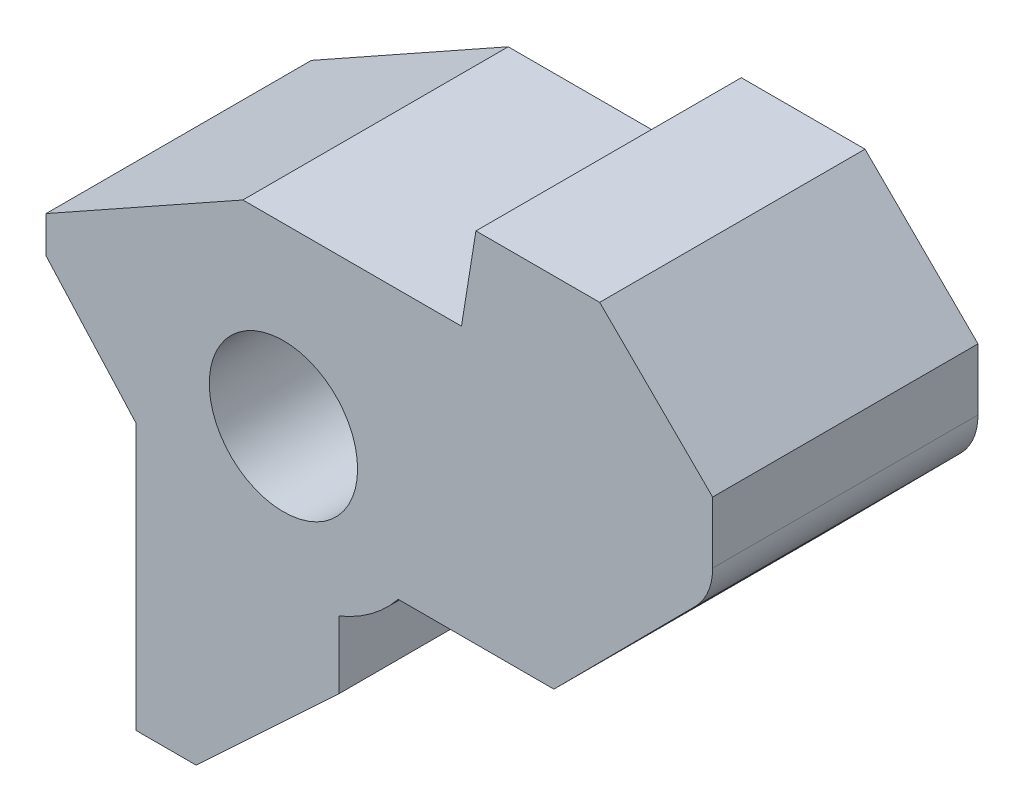
SolidWorks part; units mm, degrees
ref_plane "정면" through (0, 0, 0) normal (0, 0, 1) x (1, 0, 0)
ref_plane "윗면" through (0, 0, 0) normal (0, 1, 0) x (1, 0, 0)
ref_plane "우측면" through (0, 0, 0) normal (1, 0, 0) x (0, 0, -1)
sketch "스케치1" plane through (0, 0, 0) normal (0, 0, 1) x (1, 0, 0)
  line L0 (-5, -2.409) -> (-8.0531, 0.9786)
  line L1 (6.0379, 5.9574) -> (6.5286, 9.0015)
  line L2 (6.5286, 9.0015) -> (10.7256, 9.0015)
  line L3 (10.7256, 9.0015) -> (14.5571, 5.198)
  line L4 (14.5571, 5.198) -> (14.5571, 2.2863)
  line L5 (14.5571, 2.2863) -> (9.173, -3.1374)
  line L6 (9.173, -3.1374) -> (3.8932, -3.1374)
  line L7 (1.8761, -4.6347) -> (1.8761, -6.9239)
  line L8 (-2.9568, -11.4363) -> (-5, -11.4363)
  line L9 (-5, -11.4363) -> (-5, -2.409)
  line L10 (-2.9568, -11.4363) -> (1.8761, -6.9239)
  line L11 (6.0379, 5.9574) -> (-1.3764, 5.9574)
  line L12 (-2.9568, -11.4363) -> (-2.9568, -11.0363)
  line L13 (-8.0531, 0.9786) -> (-8.0531, 2.2192)
  line L14 (-8.0531, 2.2192) -> (-1.3764, 5.9574)
  circle A0 centre (0, 0) radius 2.515
  circle A1 centre (0, 0) radius 5
  dimension "D1" = 5.03
  dimension "D2" = 10
  dimension "D3" = 43.036
  dimension "D4" = 0.4
extrude "보스-돌출1" add sketch "스케치1" along normal blind 9
fillet "필렛1" radius 2 1 edges at (14.5571, 2.2863, 4.5)
